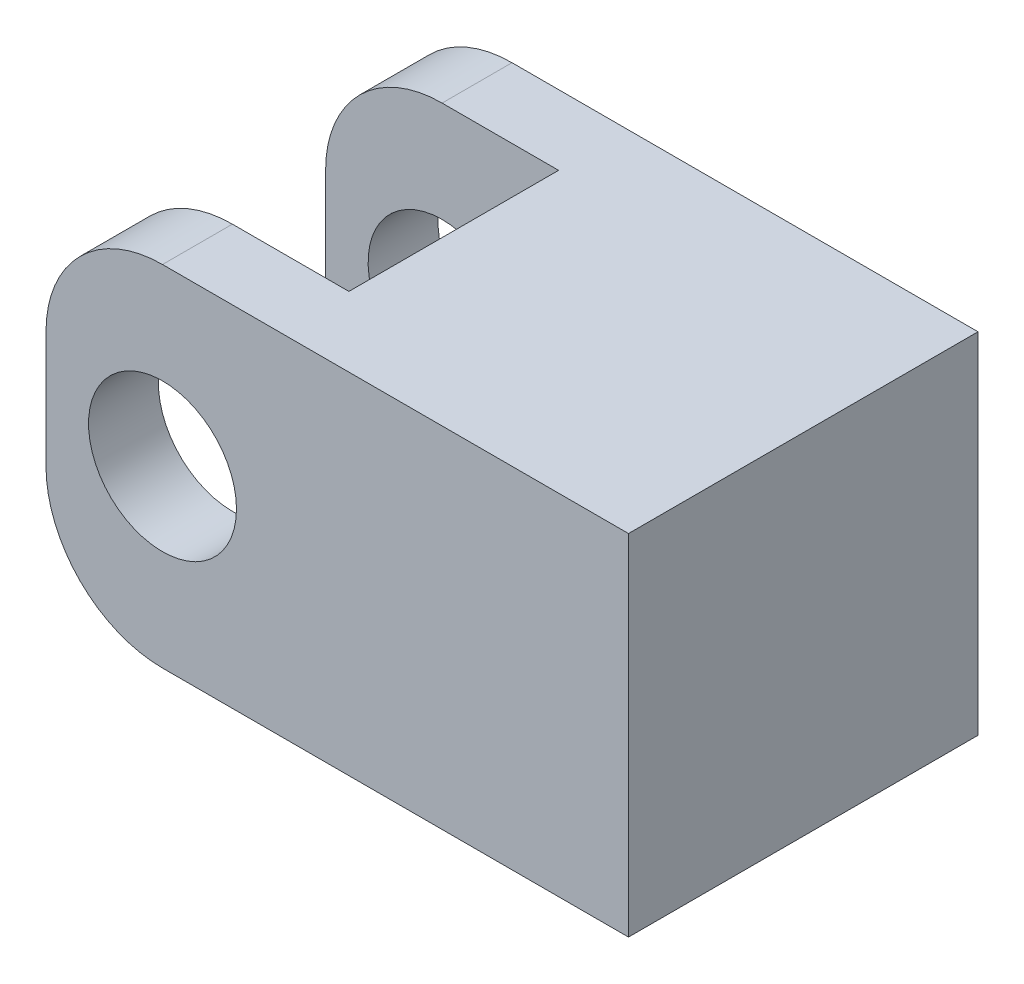
SolidWorks part; units mm, degrees
ref_plane "Front" through (0, 0, 0) normal (0, 0, 1) x (1, 0, 0)
ref_plane "Top" through (0, 0, 0) normal (0, 1, 0) x (1, 0, 0)
ref_plane "Right" through (0, 0, 0) normal (1, 0, 0) x (0, 0, -1)
sketch "Esquisse1" plane through (0, 0, 0) normal (0, 0, 1) x (1, 0, 0)
  line L1 (-25, 15) -> (25, 15)
  line L2 (-25, 15) -> (-25, -15)
  line L3 (-25, -15) -> (25, -15)
  line L4 (25, 15) -> (25, -15)
  line L5 (-25, 15) -> (25, -15) construction
  line L6 (-25, -15) -> (25, 15) construction
  point P0 (0, 0)
  dimension "D1" = 50
  dimension "D2" = 30
extrude "Boss.-Extru.1" add sketch "Esquisse1" along normal blind 30
sketch "Esquisse2" plane through (0, 0, 30) normal (0, 0, 1) x (1, 0, 0)
  line L0 (-25, 15) -> (-25, -15) construction
  line L1 (25, 15) -> (-25, 15) construction
  circle A0 centre (-15, 0) radius 6.35
  dimension "D1" = 10
  dimension "D2" = 15
extrude "Enlèv. mat.-Extru.1" cut sketch "Esquisse2" against normal up to next
fillet "Congé1" radius 10 2 edges at (-25, -15, 15) (-25, 15, 15)
sketch "Esquisse3" plane through (-25, 0, 0) normal (-1, 0, 0) x (0, 0, 1)
  line L0 (0, 15) -> (30, 15) construction
  line L1 (6, 15) -> (24, 15)
  line L2 (6, 15) -> (6, -15)
  line L3 (6, -15) -> (24, -15)
  line L4 (24, 15) -> (24, -15)
  line L5 (30, -15) -> (0, -15) construction
  line L6 (0, 15) -> (0, 5) construction
  line L7 (30, 5) -> (30, 15) construction
  dimension "D1" = 6
  dimension "D2" = 6
extrude "Enlèv. mat.-Extru.2" cut sketch "Esquisse3" against normal blind 20
